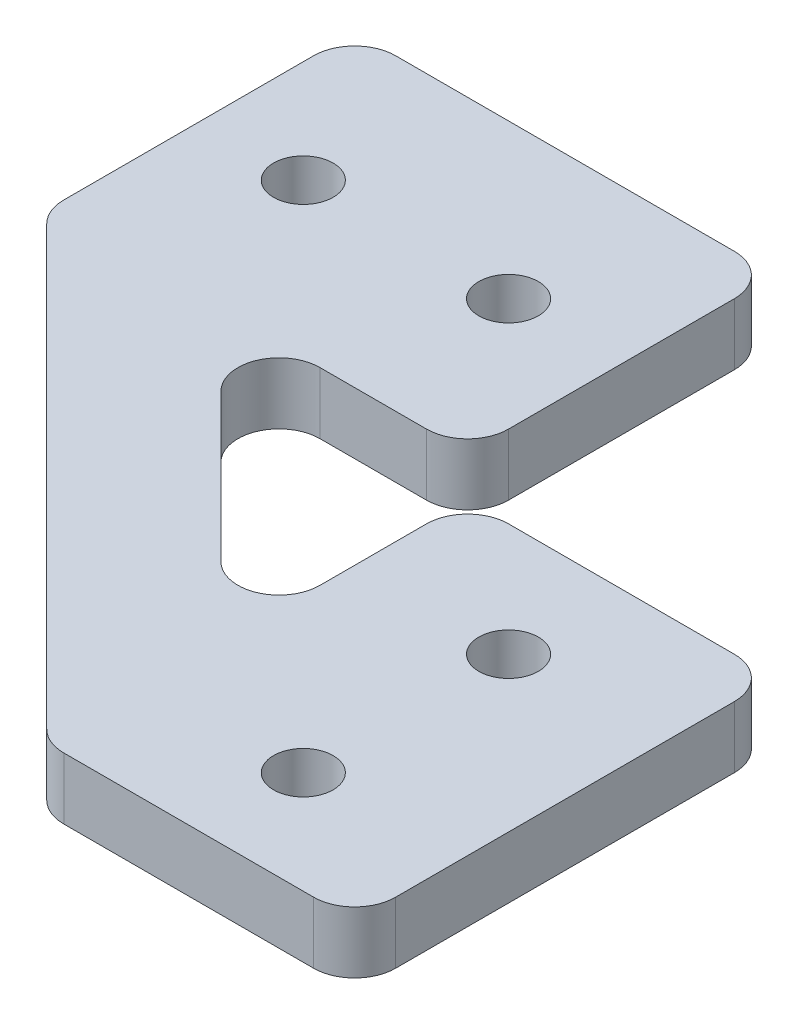
SolidWorks part; units mm, degrees
material "Thornel Mat VMA"
ref_plane "前视基准面" through (0, 0, 0) normal (0, 0, 1) x (1, 0, 0)
ref_plane "上视基准面" through (0, 0, 0) normal (0, 1, 0) x (1, 0, 0)
ref_plane "右视基准面" through (0, 0, 0) normal (1, 0, 0) x (0, 0, -1)
other "Configuration Table"
sketch "草图1" plane through (0, 0, 0) normal (0, 1, 0) x (1, 0, 0)
  line L0 (-37.5, -7.5) -> (0, -7.5) construction
  line L1 (0, 0) -> (-37.5, 0)
  line L2 (0, 0) -> (0, -37.5)
  line L3 (0, -37.5) -> (-15, -37.5)
  line L4 (-37.5, 0) -> (-37.5, -15)
  line L7 (-37.5, -15) -> (-15, -15)
  line L8 (-15, -37.5) -> (-15, -15)
  line L9 (-7.5, -37.5) -> (-7.5, 0) construction
  circle A0 centre (-7.5, -7.5) radius 1.45
  circle A1 centre (-22.5, -7.5) radius 1.45
  circle A2 centre (-32.5, -7.5) radius 1.45
  circle A3 centre (-7.5, -22.5) radius 1.45
  circle A4 centre (-7.5, -32.5) radius 1.45
  dimension "D3" = 2.9
  dimension "D4" = 2.9
  dimension "D5" = 2.9
  dimension "D6" = 7.5
  dimension "D7" = 10
  dimension "D9" = 2.9
  dimension "D10" = 2.9
  dimension "D12" = 10
  dimension "D1" = 15
  dimension "D2" = 15
  dimension "D8" = 37.5
  dimension "D11" = 7.5
  dimension "D13" = 37.5
extrude "凸台-拉伸1" add sketch "草图1" along normal blind 3
sketch "草图2" plane through (0, 3, 0) normal (0, 1, 0) x (1, 0, 0)
  line L0 (-37.5, -15) -> (-15, -37.5)
  line L1 (-15, -37.5) -> (-15, -29.0147)
  line L2 (-15, -15) -> (-15, -37.5) construction
  line L3 (-15, -29.0147) -> (-29.0147, -15)
  line L4 (-37.5, -15) -> (-15, -15) construction
  line L5 (-29.0147, -15) -> (-37.5, -15)
  dimension "D1" = 6
extrude "凸台-拉伸2" add sketch "草图2" against normal blind 3
sketch "草图3" plane through (0, 3, 0) normal (0, 1, 0) x (1, 0, 0)
  line L1 (0, 0) -> (-17, 0)
  line L2 (0, 0) -> (0, -17)
  line L3 (0, -17) -> (-17, -17)
  line L4 (-17, 0) -> (-17, -17)
  dimension "D1" = 17
  dimension "D2" = 17
extrude "切除-拉伸1" cut sketch "草图3" against normal through all
fillet "圆角1" radius 2 10 edges at (-15, 1.5, 37.5) (-37.5, 1.5, 15) (-37.5, 1.5, 0) (0, 1.5, 37.5) (-15, 1.5, 29.0147) (-29.0147, 1.5, 15) (0, 1.5, 17) (-15, 1.5, 17) (-17, 1.5, 0) (-17, 1.5, 15)
